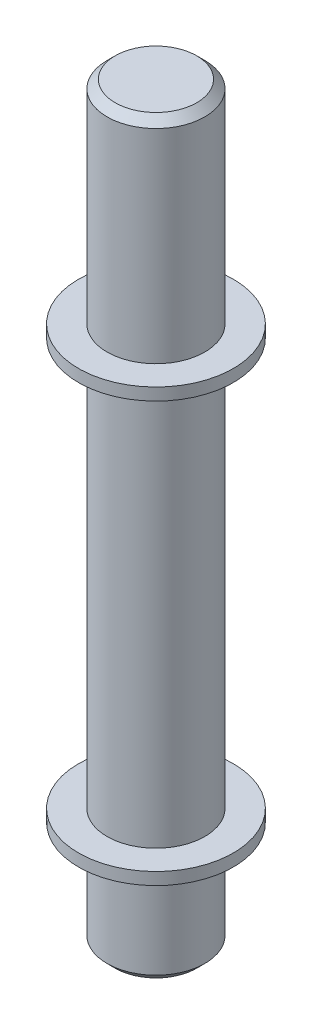
SolidWorks part; units mm, degrees
material "Alloy Steel (SS)"
ref_plane "Front Plane" through (0, 0, 0) normal (0, 0, 1) x (1, 0, 0)
ref_plane "Top Plane" through (0, 0, 0) normal (0, 1, 0) x (1, 0, 0)
ref_plane "Right Plane" through (0, 0, 0) normal (1, 0, 0) x (0, 0, -1)
sketch "Sketch1" plane through (0, 0, 0) normal (0, 0, 1) x (1, 0, 0)
  line L0 (0, 30.5527) -> (0, -22.496) construction
  line L1 (-41.7484, 0) -> (55.5598, 0) construction
  line L2 (0, 0) -> (12, 0)
  line L3 (12, 0) -> (12, 26)
  line L4 (12, 26) -> (19, 26)
  line L5 (19, 26) -> (19, 29)
  line L6 (19, 29) -> (12, 29)
  line L7 (12, 29) -> (12, 129)
  line L8 (12, 129) -> (19, 129)
  line L9 (19, 129) -> (19, 132)
  line L10 (19, 132) -> (12, 132)
  line L11 (12, 132) -> (12, 184)
  line L12 (12, 184) -> (0, 184)
  line L13 (0, 184) -> (0, 0)
  dimension "D1" = 12
  dimension "D2" = 3
  dimension "D3" = 26
  dimension "D4" = 52
  dimension "D5" = 100
  dimension "D6" = 19
revolve "Revolve1" add sketch "Sketch1" angle 360 about L13
cosmetic thread "Cosmetic Thread1" parameters "D1"=26, "D2"=20.704
cosmetic thread "Cosmetic Thread2" parameters "D1"=26, "D2"=20.704
chamfer "Chamfer1" distance 2 angle 45 2 edges at (-12, 0, 0) (-12, 184, 0)
